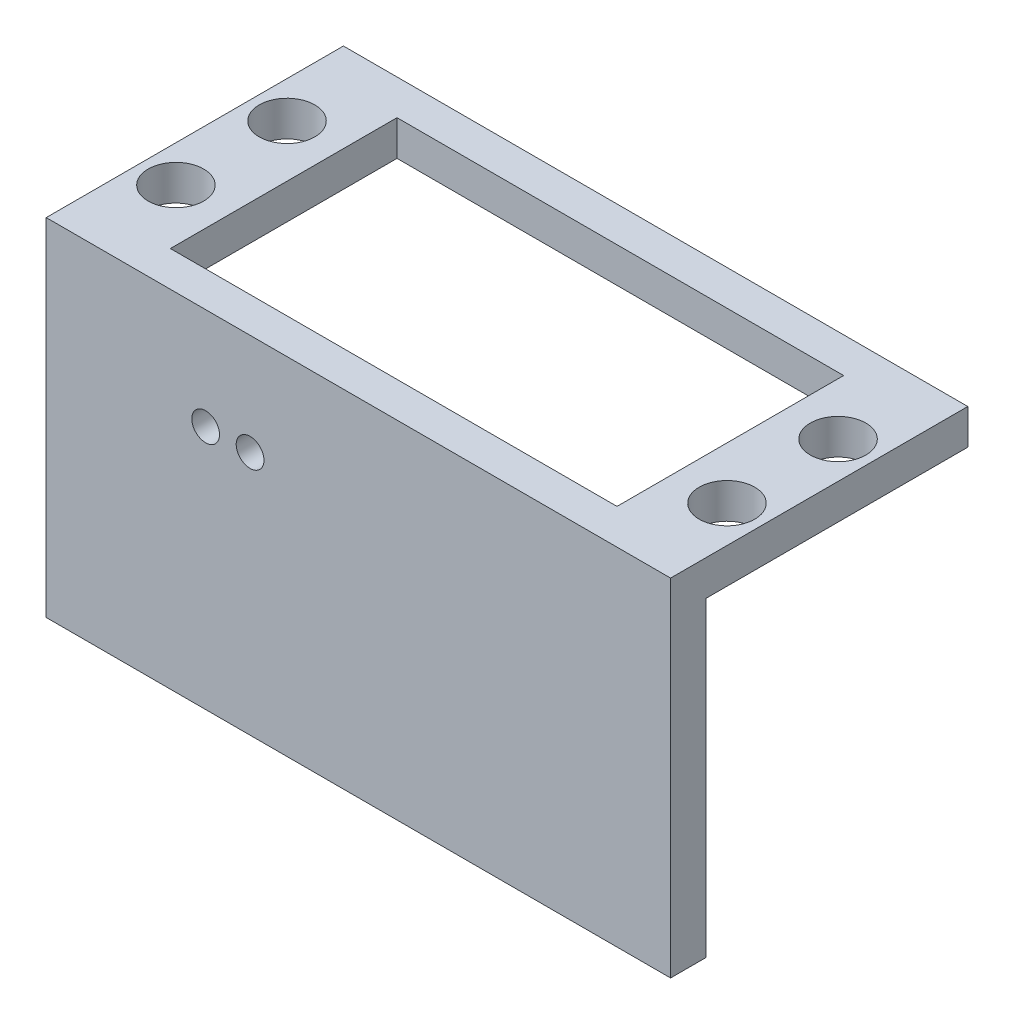
SolidWorks part; units mm, degrees
ref_plane "Front Plane" through (0, 0, 0) normal (0, 0, 1) x (1, 0, 0)
ref_plane "Top Plane" through (0, 0, 0) normal (0, 1, 0) x (1, 0, 0)
ref_plane "Right Plane" through (0, 0, 0) normal (1, 0, 0) x (0, 0, -1)
sketch "Sketch1" plane through (0, 0, 0) normal (0, 1, 0) x (1, 0, 0)
  line L0 (0, 13.375) -> (0, -13.375) construction
  line L1 (-20.1, 10.2) -> (20.1, 10.2)
  line L2 (-20.1, 10.2) -> (-20.1, -10.2)
  line L3 (-20.1, -10.2) -> (20.1, -10.2)
  line L4 (20.1, 10.2) -> (20.1, -10.2)
  line L5 (-20.1, 10.2) -> (20.1, -10.2) construction
  line L6 (-20.1, -10.2) -> (20.1, 10.2) construction
  line L7 (-28.1, 13.375) -> (28.1, 13.375)
  line L8 (-28.1, 13.375) -> (-28.1, -13.375)
  line L9 (-28.1, -13.375) -> (28.1, -13.375)
  line L10 (28.1, 13.375) -> (28.1, -13.375)
  line L11 (-28.1, 13.375) -> (28.1, -13.375) construction
  line L12 (-28.1, -13.375) -> (28.1, 13.375) construction
  circle A0 centre (24.8, 5) radius 2.5
  circle A1 centre (24.8, -5) radius 2.5
  circle A2 centre (-24.8, -5) radius 2.5
  circle A3 centre (-24.8, 5) radius 2.5
  point P0 (0, 0)
  point P6 (0, 0)
  dimension "D4" = 5
  dimension "D1" = 40.2
  dimension "D2" = 20.4
  dimension "D3" = 8
  dimension "D5" = 4.7
  dimension "D6" = 10
  dimension "D7" = 5.2
  dimension "D8" = 3.175
extrude "Boss-Extrude1" add sketch "Sketch1" along normal blind 3.175
sketch "Sketch2" plane through (0, 0, 0) normal (0, -1, 0) x (-1, 0, 0)
  line L0 (28.1, 13.375) -> (28.1, -13.375) construction
  line L1 (-28.1, -13.375) -> (28.1, -13.375)
  line L2 (-28.1, -13.375) -> (-28.1, -10.2)
  line L3 (-28.1, -10.2) -> (28.1, -10.2)
  line L4 (28.1, -13.375) -> (28.1, -10.2)
  line L5 (20.1, -10.2) -> (-20.1, -10.2) construction
extrude "Boss-Extrude2" add sketch "Sketch2" along normal blind 28
sketch "Sketch3" plane through (0, 0, 13.375) normal (0, 0, 1) x (1, 0, 0)
  line L0 (28.1, -5.9533) -> (-28.1, -5.9533) construction
  line L1 (28.1, 3.175) -> (28.1, -28) construction
  line L2 (-28.1, 3.175) -> (-28.1, -28) construction
  circle A0 centre (-9.75, -5.9533) radius 1.25
  circle A1 centre (-13.75, -5.9533) radius 1.25
  dimension "D1" = 2.5
  dimension "D2" = 4
  dimension "D3" = 37.85
extrude "Cut-Extrude1" cut sketch "Sketch3" against normal up to surface (3.175 mm away) up to face at (0, -6.2062, 10.2)
